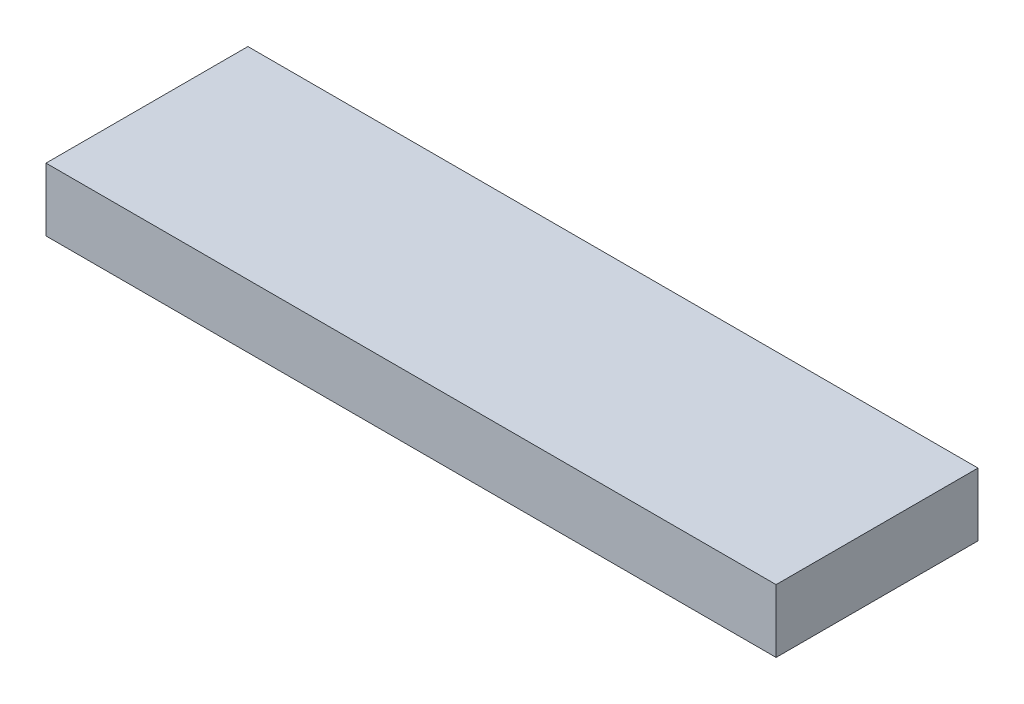
SolidWorks part; units mm, degrees
ref_plane "Спереди" through (0, 0, 0) normal (0, 0, 1) x (1, 0, 0)
ref_plane "Сверху" through (0, 0, 0) normal (0, 1, 0) x (1, 0, 0)
ref_plane "Справа" through (0, 0, 0) normal (1, 0, 0) x (0, 0, -1)
sketch "Эскиз1" plane through (0, 0, 0) normal (0, 1, 0) x (1, 0, 0)
  line L0 (0, 0) -> (-15032.7523, 0) construction
  line L1 (0, 0) -> (0, 15032.7523) construction
  line L3 (20.25, 5.6) -> (-20.25, 5.6)
  line L4 (20.25, 5.6) -> (20.25, -5.6)
  line L5 (20.25, -5.6) -> (-20.25, -5.6)
  line L6 (-20.25, 5.6) -> (-20.25, -5.6)
  line L7 (20.25, 5.6) -> (-20.25, -5.6) construction
  line L8 (20.25, -5.6) -> (-20.25, 5.6) construction
  point P5 (0, 0)
  dimension "D1" = 40.5
  dimension "D2" = 11.2
extrude "Бобышка-Вытянуть1" add sketch "Эскиз1" along normal blind 3.5
